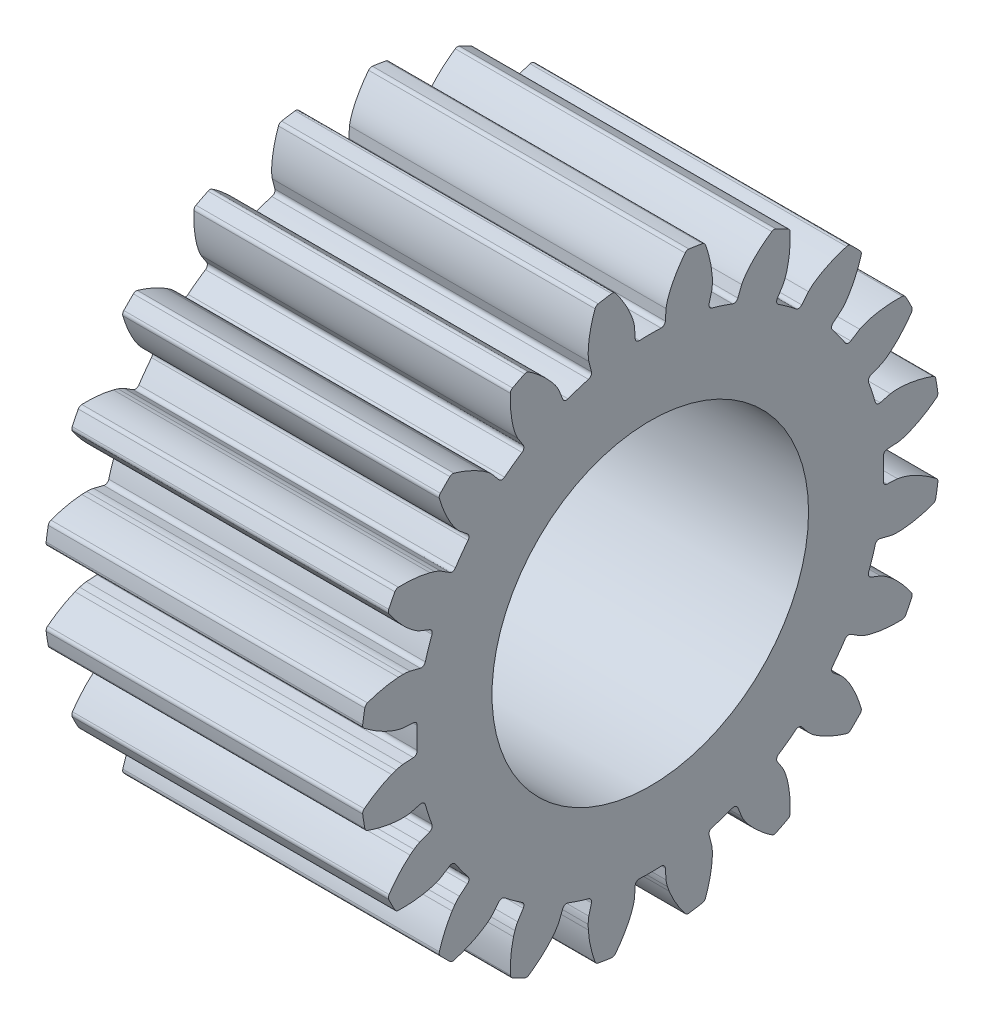
SolidWorks part; units mm, degrees
ref_plane "Front Plane" through (0, 0, 0) normal (1, 0, 0) x (0, 1, 0)
ref_plane "Top Plane" through (0, 0, 0) normal (0, 0, 1) x (0, 1, 0)
ref_plane "Right Plane" through (0, 0, 0) normal (0, 1, 0) x (-1, 0, 0)
sketch "Sketch2" plane through (0, 0, 0) normal (1, 0, 0) x (0, 1, 0)
  circle A0 centre (0, 0) radius 6.35
  circle A1 centre (0, 0) radius 11.6417
  dimension "D1" = 12.7
  dimension "D2" = 23.2833
extrude "Gear Width Extrude" add sketch "Sketch2" along normal blind 12.7
sketch "Sketch3" plane through (0, 0, 0) normal (1, 0, 0) x (0, 1, 0)
  line L0 (-11.6417, 0) -> (11.6417, 0) construction
  line L1 (0, 11.6417) -> (0, -11.6417) construction
  line L2 (0, 0) -> (9.925, 0.6324) construction
  line L5 (9.3588, 0) -> (11.6417, 0)
  line L6 (9.925, 0.6324) -> (9.3399, 0.5952)
  circle A0 centre (0, 0) radius 9.3588 construction
  circle A1 centre (0, 0) radius 9.9451 construction
  circle A2 centre (0, 0) radius 10.5833 construction
  circle A3 centre (0, 0) radius 11.6417 construction
  arc A7 (11.5501, 1.4571) -> (11.6417, 0) centre (0, 0) cw
  arc A8 (9.3399, 0.5952) -> (9.3588, 0) centre (0, 0) cw
  spline S0 degree 4 poles (9.925, 0.6324) (9.9277, 0.6326) (9.9353, 0.6333) (9.9587, 0.6362) (10.0047, 0.6437) (10.0613, 0.6559) (10.1259, 0.6725) (10.1879, 0.6907) (10.2407, 0.7075) (10.2932, 0.7255) (10.3452, 0.7445) (10.408, 0.7688) (10.4829, 0.7997) (10.5698, 0.8384) (10.6677, 0.8854) (10.7666, 0.9364) (10.8632, 0.9893) (10.96, 1.0458) (11.053, 1.1026) (11.1486, 1.1646) (11.2364, 1.2234) (11.3337, 1.2927) (11.4119, 1.3495) (11.5138, 1.4281) (11.5736, 1.4756) (11.6432, 1.5323) (11.6738, 1.5582) (11.6927, 1.5741) knots 0 0 0 0 0 0.005377 0.015084 0.04661 0.092111 0.119476 0.146842 0.174209 0.201575 0.228941 0.256307 0.307035 0.361767 0.4165 0.471232 0.525964 0.580697 0.635429 0.690161 0.744894 0.799626 0.854358 0.909091 0.954545 1 1 1 1 1 construction
  spline S1 degree 4 poles (9.925, 0.6324) (9.9277, 0.6326) (9.9353, 0.6333) (9.9587, 0.6362) (10.0047, 0.6437) (10.0613, 0.6559) (10.1259, 0.6725) (10.1879, 0.6907) (10.2407, 0.7075) (10.2932, 0.7255) (10.3452, 0.7445) (10.408, 0.7688) (10.4829, 0.7997) (10.5698, 0.8384) (10.6677, 0.8854) (10.7666, 0.9364) (10.8632, 0.9893) (10.96, 1.0458) (11.053, 1.1026) (11.1486, 1.1646) (11.2364, 1.2234) (11.3337, 1.2927) (11.4119, 1.3495) (11.4917, 1.4111) (11.5304, 1.4414) (11.5501, 1.4571) knots 0 0 0 0 0 0.005377 0.015084 0.04661 0.092111 0.119476 0.146842 0.174209 0.201575 0.228941 0.256307 0.307035 0.361767 0.4165 0.471232 0.525964 0.580697 0.635429 0.690161 0.744894 0.799626 0.854358 0.909091 0.909091 0.909091 0.909091 0.909091
  dimension "D1" = 21.1667
  dimension "D2" = 19.8902
  dimension "D3" = 18.7177
extrude "Gear Tooth Cut" cut sketch "Sketch3" along normal blind 25.4
mirror "Gear Tooth Cut Mirror" of "Gear Tooth Cut"
fillet "Tooth Fillets" radius 0.1662 4 edges at (6.35, 11.5501, 1.4571) (6.35, 11.5501, -1.4571) (6.35, 9.3399, 0.5952) (6.35, 9.3399, -0.5952)
pattern_circular "CirPattern1" count 20 over 360 about axis through (0, 0, 0) along (1, 0, 0) of "Gear Tooth Cut", "Gear Tooth Cut Mirror", "Tooth Fillets"
sketch "Sketch4" plane through (12.7, 0, 0) normal (1, 0, 0) x (0, 1, 0)
  circle A0 centre (0, 0) radius 10.4064
  circle A2 centre (0, 0) radius 10.2159
  dimension "D1" = 20.8128
  dimension "D2" = 0.1905
split line "Split Line1"
equation "\"DP\"= 24'INPUT: Diametral Pitch"
equation "\"a_Pressure\"= 20'INPUT: Pressure Angle"
equation "\"Z\"= 20'INPUT: Number of Teeth"
equation "\"w_Face\"= 0.5'INPUT: Face Width"
equation "\"d_Bore\"= 1 / 2'INPUT: Bore Diameter"
equation "\"d_Pitch\"= \"Z\" / \"DP\"'Pitch Diameter"
equation "\"Module\"= 1 / \"DP\"'Module"
equation "\"d_Base\"= \"d_Pitch\" * cos ( \"a_Pressure\" )'Base Circle Diameter"
equation "\"Clearance\"= 0.157 / \"DP\"'Clearance"
equation "\"CP\"= pi * \"d_Pitch\" / \"Z\"'Circular Pitch"
equation "\"h_Addendum\"= 1 / \"DP\"'Addendum Depth"
equation "\"h_Dedendum\"= IIF ( \"h_deStandard\" > \"h_deMin\" , \"h_deStandard\" , \"h_deMin\" )'Dedendum Depth"
equation "\"d_Addendum\"= \"d_Pitch\" + ( 2 * \"h_Addendum\" )'Addendum (Tip) Diameter"
equation "\"d_Dedendum\"= \"d_Pitch\" - ( 2 * \"h_Dedendum\" )'Dedendum (Root) Diameter"
equation "\"a_Pitch\"= 360 / \"Z\"'Pitch Angle"
equation "\"a_Alpha\"= ( ( 180 * ( ( \"d_Pitch\" ^ 2 ) - ( \"d_Base\" ^ 2 ) ) ^ 0.5 ) / ( pi * \"d_Base\" ) ) - \"a_Pressure\"'Alpha Angle"
equation "\"a_Beta\"= ( \"a_Pitch\" / 4 ) - \"a_Alpha\"'Beta Angle"
equation "\"ICDP\"= ( ( ( \"d_Addendum\" / 2 ) ^ 2 - ( \"d_Base\" / 2 ) ^ 2 ) ^ 0.5 ) * ( 2 / \"d_Base\" )'Involute Curve Domain Parameter"
equation "\"D1@Sketch2\"=\"d_Bore\""
equation "\"D2@Sketch2\"=\"d_Addendum\""
equation "\"D1@Gear Width Extrude\" = \"w_Face\""
equation "\"D1@Sketch3\"=\"d_Pitch\""
equation "\"D2@Sketch3\"=\"d_Base\""
equation "\"D3@Sketch3\"= \"d_Dedendum\""
equation "\"D1@CirPattern1\"=\"Z\""
equation "\"D1@Tooth Fillets\"=\"Clearance\""
equation "\"h_deStandard\"= ( 1 / \"DP\" ) + \"Clearance\""
equation "\"h_deMin\"= ( \"d_Pitch\" * ( 1 - cos ( \"a_Pressure\" ) ) / 2 ) + \"Clearance\""
